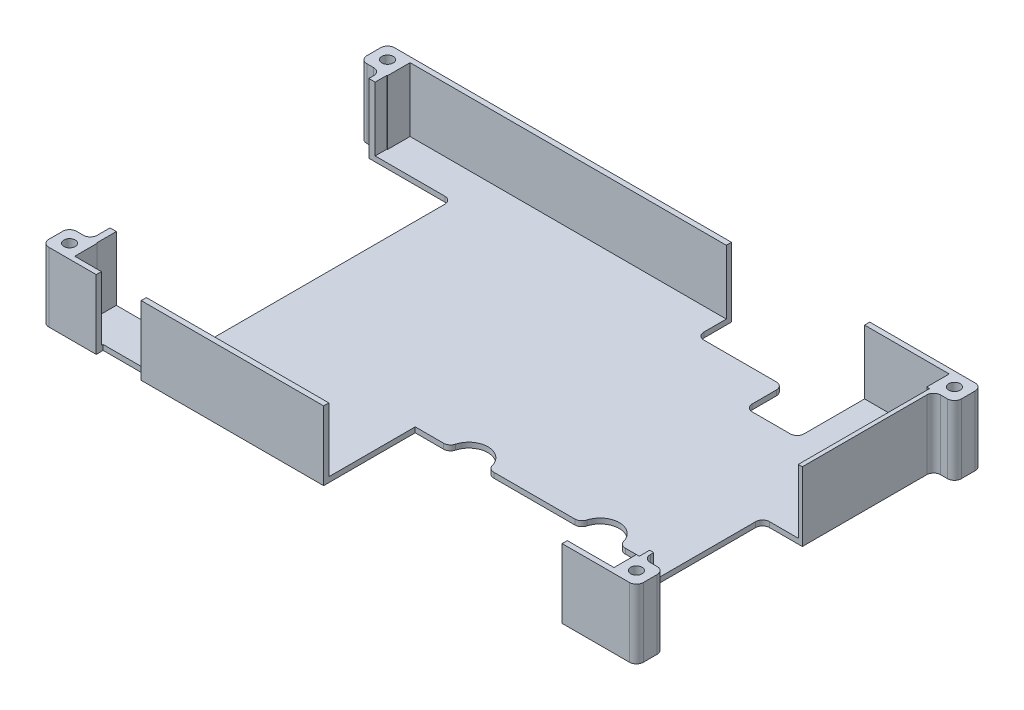
SolidWorks part; units mm, degrees
ref_plane "Front Plane" through (0, 0, 0) normal (0, 0, 1) x (1, 0, 0)
ref_plane "Top Plane" through (0, 0, 0) normal (0, 1, 0) x (1, 0, 0)
ref_plane "Right Plane" through (0, 0, 0) normal (1, 0, 0) x (0, 0, -1)
sketch "Sketch1" plane through (0, 0, 0) normal (0, 1, 0) x (1, 0, 0)
  line L1 (0, 0) -> (160, 0)
  line L2 (0, 0) -> (0, 100)
  line L3 (0, 100) -> (160, 100)
  line L4 (160, 0) -> (160, 100)
  dimension "D1" = 160
  dimension "D2" = 100
extrude "Boss-Extrude1" add sketch "Sketch1" along normal blind 1.5
sketch "Sketch2" plane through (0, 0, 0) normal (0, 1, 0) x (1, 0, 0)
  line L0 (160, 78.8862) -> (158.8264, 78.8862) construction
  line L1 (160, 0) -> (0, 0)
  line L2 (160, 0) -> (160, 100)
  line L3 (160, 100) -> (0, 100)
  line L4 (0, 0) -> (0, 100)
  line L5 (158.8264, 100) -> (158.8264, 98.5) construction
  line L7 (158.8264, 98.5) -> (1.8264, 98.5)
  line L8 (158.8264, 98.5) -> (158.8264, 1.5)
  line L9 (158.8264, 1.5) -> (1.8264, 1.5)
  line L10 (1.8264, 98.5) -> (1.8264, 1.5)
  dimension "D1" = 157
  dimension "D2" = 97
extrude "Boss-Extrude2" add sketch "Sketch2" along normal blind 20
fillet "Fillet1" radius 2 4 edges at (0, 10, -100) (160, 10, -100) (160, 10, 0) (0, 10, 0)
sketch "Sketch4" plane through (0, 0, 0) normal (0, -1, 0) x (1, 0, 0)
  line L0 (160, -94.7257) -> (133.5, -94.7257) construction
  line L1 (160, -2) -> (160, -98) construction
  line L2 (158, -100) -> (2, -100) construction
  line L3 (133.5, -100) -> (118.5, -100)
  line L4 (133.5, -100) -> (133.5, -79)
  line L5 (133.5, -79) -> (118.5, -79)
  line L6 (118.5, -100) -> (118.5, -79)
  dimension "D1" = 26.5
  dimension "D2" = 21
  dimension "D3" = 15
extrude "Cut-Extrude1" cut sketch "Sketch4" against normal through all
sketch "Sketch5" plane through (0, 0, 0) normal (0, -1, 0) x (1, 0, 0)
  line L0 (160, -9.2111) -> (144.5, -9.2111) construction
  line L1 (160, -2) -> (160, -98) construction
  line L2 (144.5, 0) -> (144.5, -26.5) construction
  line L3 (2, 0) -> (158, 0) construction
  line L5 (144.5, 0) -> (75.5, 0)
  line L6 (144.5, 0) -> (144.5, -26.5)
  line L7 (144.5, -26.5) -> (75.5, -26.5)
  line L8 (75.5, 0) -> (75.5, -26.5)
  dimension "D1" = 15.5
  dimension "D2" = 26.5
  dimension "D3" = 69
extrude "Cut-Extrude2" cut sketch "Sketch5" against normal through all
sketch "Sketch6" plane through (0, 0, 0) normal (0, -1, 0) x (1, 0, 0)
  line L0 (151.25, 0) -> (151.25, -11) construction
  line L1 (144.5, 0) -> (158, 0) construction
  line L2 (160, -11) -> (148.5, -11) construction
  line L3 (160, -2) -> (160, -98) construction
  line L5 (148.5, -11) -> (160, -11)
  line L6 (148.5, -11) -> (148.5, -54)
  line L7 (148.5, -54) -> (160, -54)
  line L8 (160, -11) -> (160, -54)
  dimension "D1" = 11
  dimension "D2" = 11.5
  dimension "D3" = 43
extrude "Cut-Extrude3" cut sketch "Sketch6" against normal through all
sketch "Sketch9" plane through (0, 0, 0) normal (0, -1, 0) x (1, 0, 0)
  line L0 (160, -11) -> (160, -54) construction
  line L1 (160, -26.5) -> (129, -26.5) construction
  line L2 (75.5, -26.5) -> (144.5, -26.5) construction
  line L3 (134.5394, -26.5) -> (123.4606, -26.5)
  line L4 (129, -26.5) -> (91, -26.5) construction
  line L6 (96.539, -26.5) -> (85.461, -26.5)
  arc A0 (134.5394, -26.5) -> (123.4606, -26.5) centre (129, -26.5) cw
  arc A1 (96.539, -26.5) -> (85.461, -26.5) centre (91, -26.5) cw
  dimension "D1" = 38
extrude "Cut-Extrude5" cut sketch "Sketch9" against normal blind 10
fillet "Fillet2" radius 2 4 edges at (85.461, 0.75, -26.5) (96.539, 0.75, -26.5) (123.4606, 0.75, -26.5) (134.5394, 0.75, -26.5)
sketch "Sketch10" plane through (0, 0, 0) normal (0, -1, 0) x (1, 0, 0)
  line L0 (2, 0) -> (75.5, 0) construction
  line L1 (22.7088, 0) -> (9.7088, 0)
  line L2 (22.7088, 0) -> (22.7088, -2)
  line L3 (22.7088, -2) -> (9.7088, -2)
  line L4 (9.7088, 0) -> (9.7088, -2)
  dimension "D1" = 13
  dimension "D2" = 2
extrude "Cut-Extrude6" cut sketch "Sketch10" against normal blind 20
fillet "Fillet4" radius 2 4 edges at (148.5, 0.75, -11) (148.5, 0.75, -54) (133.5, 0.75, -79) (118.5, 0.75, -79)
sketch "Sketch11" plane through (0, 0, 0) normal (0, -1, 0) x (1, 0, 0)
  line L1 (118.5, -100) -> (93.5, -100)
  line L2 (118.5, -100) -> (118.5, -90)
  line L3 (118.5, -90) -> (93.5, -90)
  line L4 (93.5, -100) -> (93.5, -90)
  dimension "D1" = 25
  dimension "D2" = 10
extrude "Cut-Extrude7" cut sketch "Sketch11" against normal blind 20
fillet "Fillet5" radius 2 2 edges at (118.5, 0.75, -90) (93.5, 0.75, -90)
sketch "Sketch12" plane through (0, 0, 0) normal (0, -1, 0) x (1, 0, 0)
  line L0 (160, -98) -> (0, -98) construction
  line L1 (0, -98) -> (0, -2) construction
  line L2 (0, -98) -> (80, -100) construction
  line L3 (93.5, -100) -> (2, -100) construction
  line L4 (80, -100) -> (80, 0) construction
  line L5 (2, -8) -> (-6, -8)
  line L6 (166, -100) -> (158, -100)
  line L7 (166, -100) -> (166, -92)
  line L8 (166, -92) -> (158, -92)
  line L9 (158, -100) -> (158, -92)
  line L10 (158, 0) -> (166, 0)
  line L11 (158, 0) -> (158, -8)
  line L12 (158, -8) -> (166, -8)
  line L13 (166, 0) -> (166, -8)
  line L14 (-6, 0) -> (-6, -8)
  line L15 (2, 0) -> (-6, 0)
  line L16 (2, 0) -> (2, -8)
  line L17 (-6, -92) -> (2, -92)
  line L18 (2, -100) -> (2, -92)
  line L19 (-6, -100) -> (2, -100)
  line L20 (-6, -100) -> (-6, -92)
  line L21 (160, -54) -> (160, -98) construction
  circle A0 centre (162, -96) radius 1.65
  circle A1 centre (162, -4) radius 1.65
  circle A2 centre (-2, -4) radius 1.65
  circle A3 centre (-2, -96) radius 1.65
  dimension "D5" = 3.3
  dimension "D1" = 8
  dimension "D2" = 8
  dimension "D3" = 8
  dimension "D4" = 8
  dimension "D6" = 2
extrude "Boss-Extrude3" add sketch "Sketch12" against normal blind 20
fillet "Fillet6" radius 2 12 edges at (160, 10, -92) (166, 10, -92) (166, 10, -100) (166, 10, -8) (160, 10, -8) (166, 10, 0) (0, 10, -8) (-6, 10, -8) (-6, 10, 0) (-6, 10, -92) (0, 10, -92) (-6, 10, -100)
sketch "Sketch14" plane through (0, 0, 0) normal (0, -1, 0) x (1, 0, 0)
  line L0 (0, -90) -> (0, -10) construction
  line L1 (0, -83.5838) -> (24, -83.5838)
  line L2 (0, -83.5838) -> (0, -18.7071)
  line L3 (0, -18.7071) -> (24, -18.7071)
  line L4 (24, -83.5838) -> (24, -18.7071)
  dimension "D1" = 24
  dimension "D2" = 64.8767
extrude "Cut-Extrude8" cut sketch "Sketch14" against normal blind 22
sketch "Sketch16" plane through (0, 0, 0) normal (0, -1, 0) x (1, 0, 0)
  line L0 (0, -90) -> (0, -83.5838) construction
  line L1 (24, -83.5838) -> (0, -83.5838)
  line L2 (24, -83.5838) -> (24, -88.5838)
  line L3 (24, -88.5838) -> (0, -88.5838)
  line L4 (0, -83.5838) -> (0, -88.5838)
  dimension "D1" = 5
extrude "Cut-Extrude9" cut sketch "Sketch16" against normal blind 20
fillet "Fillet8" radius 2 1 edges at (24, 0.75, -88.5838)
sketch "Sketch18" plane through (0, 0, 0) normal (0, -1, 0) x (1, 0, 0)
  line L0 (0, -18.7071) -> (0, -10) construction
  line L1 (24, -18.7071) -> (0, -18.7071)
  line L2 (24, -18.7071) -> (24, -13.7071)
  line L3 (24, -13.7071) -> (0, -13.7071)
  line L4 (0, -18.7071) -> (0, -13.7071)
  dimension "D1" = 5
extrude "Cut-Extrude10" cut sketch "Sketch18" against normal blind 20
fillet "Fillet9" radius 2 1 edges at (24, 0.75, -13.7071)
